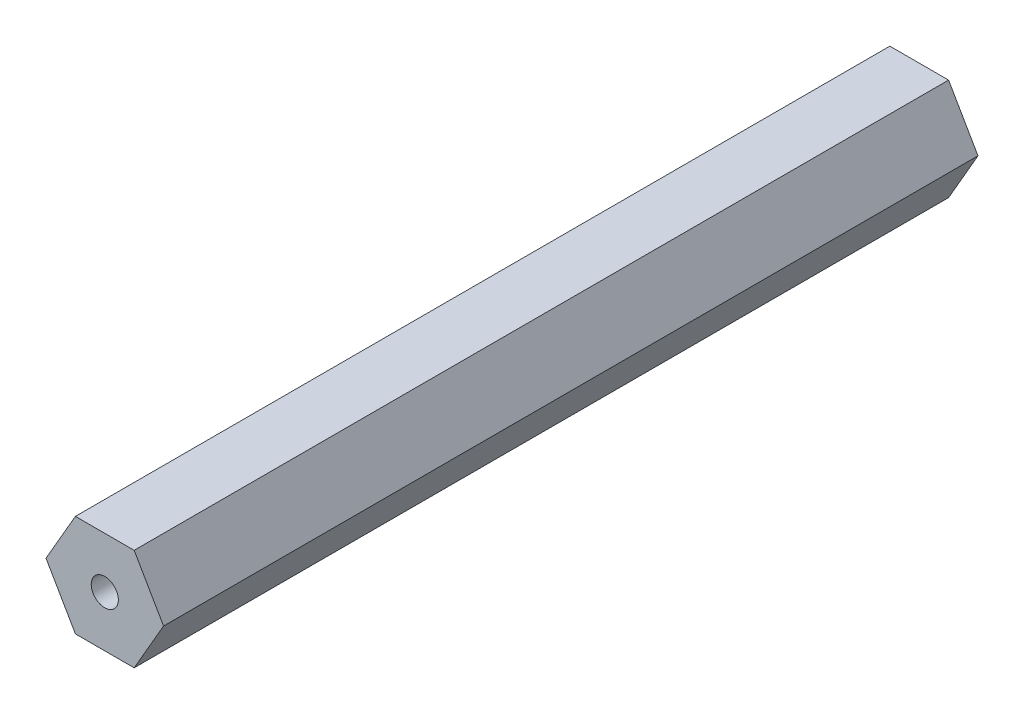
SolidWorks part; units mm, degrees
ref_plane "Front Plane" through (0, 0, 0) normal (0, 0, 1) x (1, 0, 0)
ref_plane "Top Plane" through (0, 0, 0) normal (0, 1, 0) x (1, 0, 0)
ref_plane "Right Plane" through (0, 0, 0) normal (1, 0, 0) x (0, 0, -1)
sketch "Sketch1" plane through (0, 0, 0) normal (0, 0, 1) x (1, 0, 0)
  line L1 (16.408, -2.6676) -> (13.6584, 2.0949)
  line L2 (13.6584, 2.0949) -> (8.1591, 2.0949)
  line L3 (8.1591, 2.0949) -> (5.4095, -2.6676)
  line L4 (5.4095, -2.6676) -> (8.1591, -7.4301)
  line L5 (8.1591, -7.4301) -> (13.6584, -7.4301)
  line L6 (13.6584, -7.4301) -> (16.408, -2.6676)
  circle A0 centre (10.9088, -2.6676) radius 4.7625 construction
  circle A1 centre (10.9088, -2.6676) radius 1.27
  dimension "D1" = 9.525
extrude "Boss-Extrude1" add sketch "Sketch1" along normal blind 76.2
